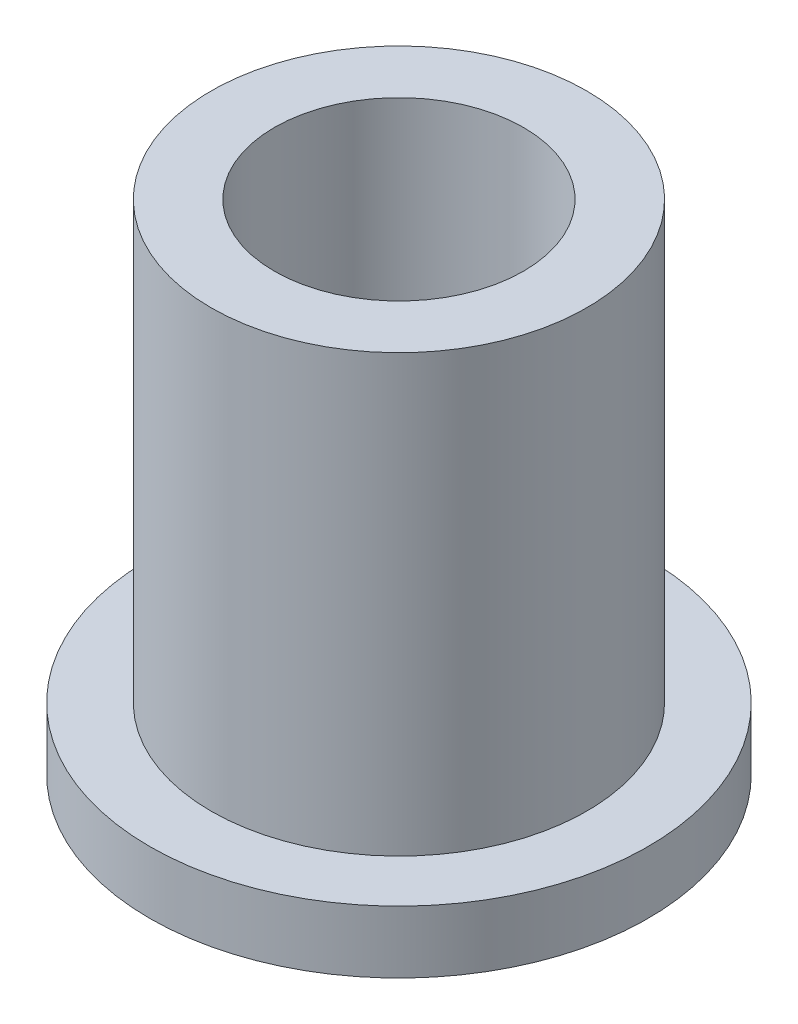
SolidWorks part; units mm, degrees
material "Tin Bearing Bronze"
ref_plane "Front" through (0, 0, 0) normal (0, 0, 1) x (1, 0, 0)
ref_plane "Top" through (0, 0, 0) normal (0, 1, 0) x (1, 0, 0)
ref_plane "Right" through (0, 0, 0) normal (1, 0, 0) x (0, 0, -1)
sketch "Sketch1" plane through (0, 0, 0) normal (0, 1, 0) x (1, 0, 0)
  circle A0 centre (0, 0) radius 3.175
  circle A1 centre (0, 0) radius 4.7879
  circle A2 centre (0, 0) radius 6.35
  dimension "ID" = 6.35
  dimension "OD" = 9.5758
  dimension "FlangeOD" = 12.7
sketch "Sketch2" plane through (0, 0, 0) normal (0, 1, 0) x (1, 0, 0)
  circle A0 centre (0, 0) radius 3.175 construction
  circle A1 centre (0, 0) radius 4.7879 construction
  circle A2 centre (0, 0) radius 3.175
  circle A3 centre (0, 0) radius 4.7879
extrude "Boss-Extrude1" add sketch "Sketch2" along normal blind 12.7
sketch "Sketch3" plane through (0, 0, 0) normal (0, 1, 0) x (1, 0, 0)
  circle A0 centre (0, 0) radius 6.35 construction
  circle A1 centre (0, 0) radius 4.7879 construction
  circle A2 centre (0, 0) radius 6.35
  circle A3 centre (0, 0) radius 4.7879
extrude "Boss-Extrude2" add sketch "Sketch3" along normal blind 1.5875
